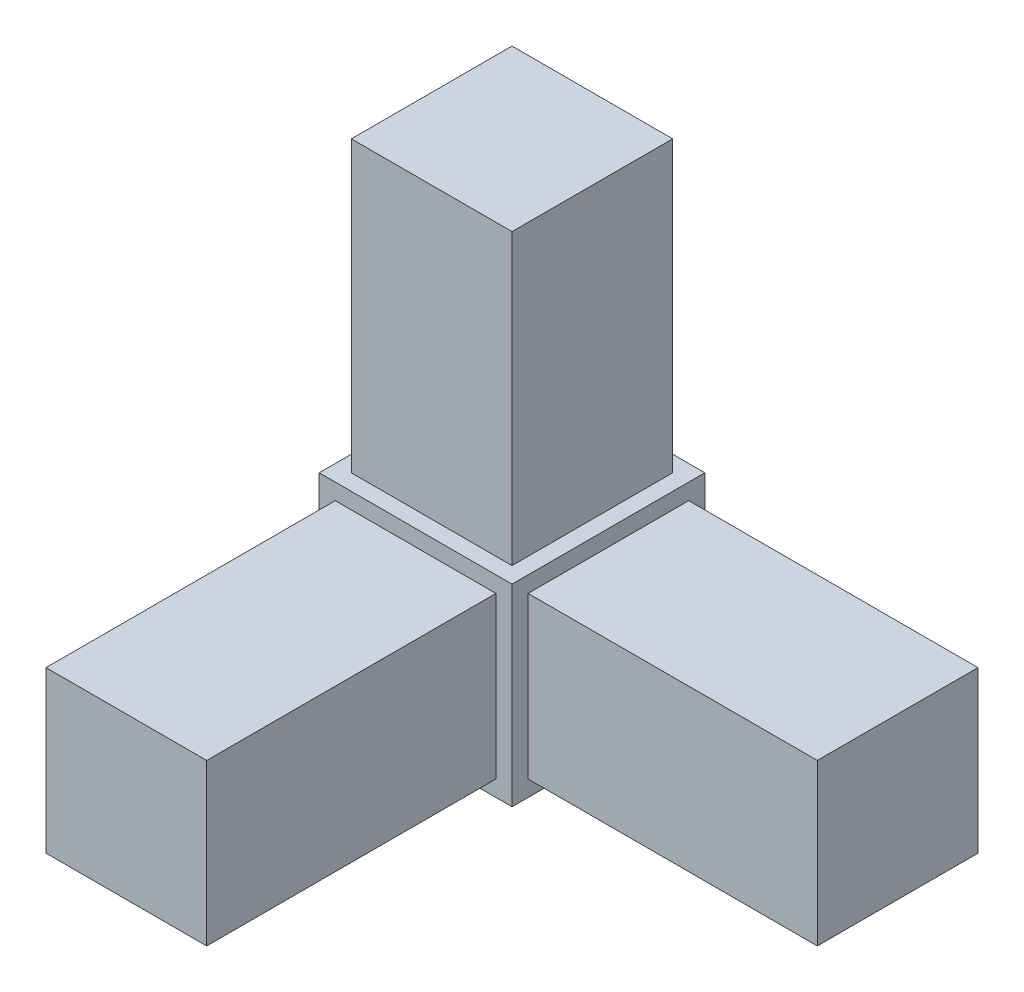
SolidWorks part; units mm, degrees
material "ABS"
ref_plane "Front Plane" through (0, 0, 0) normal (0, 0, 1) x (1, 0, 0)
ref_plane "Top Plane" through (0, 0, 0) normal (0, 1, 0) x (1, 0, 0)
ref_plane "Right Plane" through (0, 0, 0) normal (1, 0, 0) x (0, 0, -1)
sketch "Sketch1" plane through (0, 0, 0) normal (0, 0, 1) x (1, 0, 0)
  line L1 (9.525, -9.525) -> (-9.525, -9.525)
  line L2 (9.525, -9.525) -> (9.525, 9.525)
  line L3 (9.525, 9.525) -> (-9.525, 9.525)
  line L4 (-9.525, -9.525) -> (-9.525, 9.525)
  line L5 (9.525, -9.525) -> (-9.525, 9.525) construction
  line L6 (9.525, 9.525) -> (-9.525, -9.525) construction
  point P0 (0, 0)
  dimension "D1" = 19.05
extrude "Boss-Extrude1" add sketch "Sketch1" along normal blind 19.05
sketch "Sketch2" plane through (0, 9.525, 0) normal (0, 1, 0) x (1, 0, 0)
  line L0 (-9.525, 0) -> (9.525, -19.05) construction
  line L2 (-7.9375, -1.5875) -> (7.9375, -1.5875)
  line L3 (-7.9375, -1.5875) -> (-7.9375, -17.4625)
  line L4 (-7.9375, -17.4625) -> (7.9375, -17.4625)
  line L5 (7.9375, -1.5875) -> (7.9375, -17.4625)
  line L6 (-7.9375, -1.5875) -> (7.9375, -17.4625) construction
  line L7 (-7.9375, -17.4625) -> (7.9375, -1.5875) construction
  point P4 (0, -9.525)
  dimension "D1" = 15.875
extrude "Boss-Extrude2" add sketch "Sketch2" along normal blind 28.575
sketch "Sketch3" plane through (9.525, 0, 0) normal (1, 0, 0) x (0, 0, -1)
  line L0 (-19.05, 9.525) -> (0, -9.525) construction
  line L2 (-17.4625, -7.9375) -> (-1.5875, -7.9375)
  line L3 (-17.4625, -7.9375) -> (-17.4625, 7.9375)
  line L4 (-17.4625, 7.9375) -> (-1.5875, 7.9375)
  line L5 (-1.5875, -7.9375) -> (-1.5875, 7.9375)
  line L6 (-17.4625, -7.9375) -> (-1.5875, 7.9375) construction
  line L7 (-17.4625, 7.9375) -> (-1.5875, -7.9375) construction
  point P4 (-9.525, 0)
  dimension "D1" = 15.875
extrude "Boss-Extrude3" add sketch "Sketch3" along normal blind 28.575
sketch "Sketch4" plane through (0, 0, 19.05) normal (0, 0, 1) x (1, 0, 0)
  line L0 (-9.525, 9.525) -> (9.525, -9.525) construction
  line L2 (7.9375, -7.9375) -> (-7.9375, -7.9375)
  line L3 (7.9375, -7.9375) -> (7.9375, 7.9375)
  line L4 (7.9375, 7.9375) -> (-7.9375, 7.9375)
  line L5 (-7.9375, -7.9375) -> (-7.9375, 7.9375)
  line L6 (7.9375, -7.9375) -> (-7.9375, 7.9375) construction
  line L7 (7.9375, 7.9375) -> (-7.9375, -7.9375) construction
  point P4 (0, 0)
  dimension "D1" = 15.875
extrude "Boss-Extrude4" add sketch "Sketch4" along normal blind 28.575
equation "\"Height\"= 32in"
equation "\"Width\"= 23in"
equation "\"Depth\"= 20in"
equation "\"Plexi\"= .121in"
equation "\"MagnetThickness\"=3mm"
equation "\"MagnetDiameter\"=12mm"
equation "\"DoorPlexi\" = \"Plexi\""
equation "\"BasePlateThickness\" = 0.5in"
equation "\"BasePlateWidth\" = \"Width\"+\"EBWidth\"-2*\"Plexi\""
equation "\"BasePlateDepth\" = \"Depth\"-\"Plexi\"-\"DoorPlexi\""
equation "\"Boxsize\" = .75in"
equation "\"Boxinner\" = .625in"
equation "\"CornerCube\" = 0.75in"
equation "\"FingerLength\" = 1.125in"
equation "\"Cutwidth\"= .016in"
equation "\"Earsize\"= 1in + \"Cutwidth\" /2"
equation "\"Slotsize\" = 1in - \"CutWidth\" / 2"
equation "\"InnerWidth\" = \"Width\" - 2* \"Plexi\""
equation "\"InnerHeight\" = \"Height\" -2 * \"Plexi\""
equation "\"InnerDepth\" = \"Depth\" - 2*\"Plexi\""
equation "\"RearNumHoles\" = 7"
equation "\"RearHolesBorder\" = 2.2"
equation "\"RearHoleSpacing\" = (\"Width\" - 2*\"RearHolesBorder\") / (\"RearNumHoles\"-1)"
equation "\"RearBarLength\" = (\"InnerWidth\"-2*\"CornerCube\")"
equation "\"RearTopNumHoles\" = 6"
equation "\"RearTopHolesBorder\" = 2.5"
equation "\"RearTopHolesSpacing\" = (\"Width\" - 2*\"RearTopHolesBorder\") / (\"RearTopNumHoles\"-1)"
equation "\"SideTopNumHoles\" = 5"
equation "\"SideTopHoleOffset\"=\"CornerCube\"+\"FingerLength\"+\"Plexi\"+.5"
equation "\"SideTopHoleSpacing\" = (\"TopBarDepth\"-2*\"SideTopHoleOffset\") / (\"SideTopNumHoles\"-1)"
equation "\"SideHorizNumHoles\" = 6"
equation "\"SideHorizHoleBorder\" = 2.25"
equation "\"SideHorizHoleSpacing\" = (\"TopBarDepth\"-2*\"SideHorizHoleBorder\") / (\"SideHorizNumHoles\"-1)"
equation "\"SideVertBarLength\"=\"Height\"-\"BasePlateThickness\"-2*\"CornerCube\"-\"Plexi\""
equation "\"SideVertNumHoles\" = 6"
equation "\"SideVertHolesBorder\" = \"CornerCube\"+\"FingerLength\"+.9"
equation "\"SideVertHoleSpacing\" = (\"InnerHeight\" - 2*\"SideVertHolesBorder\") / (\"SideVertNumHoles\"-1)"
equation "\"RearSideVertNumHoles\" = 7"
equation "\"RearSideVertHolesBorder\" = 2.5"
equation "\"RearSideVertHoleSpacing\" = (\"InnerHeight\" - 2*\"RearSideVertHolesBorder\") / (\"RearSideVertNumHoles\"-1)"
equation "\"RivetDia\" = .228in"
equation "\"SlotDepth\" = \"Plexi\" + 0.75in + .005in"
equation "\"SideSlotWidth\"   = \"Plexi\"+.005in"
equation "\"SidePanelVertSpacing\" = (\"Height\"-2*(1.75-\"Plexi\")) / 5"
equation "\"BottomPanelSideHoleSpacing\" = (\"InnerDepth\"-2*(1.75-\"Plexi\")) / 4"
equation "\"FrontDoorGap\" = .1in"
equation "\"TopDepth\" = \"Depth\"-\"DoorPlexi\"-\"FrontDoorGap\""
equation "\"TopBarDepth\" = \"Depth\"-\"DoorPlexi\"-\"Plexi\"-2*\"MagnetThickness\"-2*\"CornerCube\""
equation "\"D1@Boss-Extrude1\"=\"CornerCube\""
equation "\"D1@Sketch1\"=\"CornerCube\""
equation "\"D1@Boss-Extrude4\"=\"FingerLength\""
equation "\"D1@Boss-Extrude3\"=\"FingerLength\""
equation "\"D1@Boss-Extrude2\"=\"FingerLength\""
equation "\"D1@Sketch2\"=\"Boxinner\""
equation "\"D1@Sketch3\"=\"Boxinner\""
equation "\"D1@Sketch4\"=\"Boxinner\""
